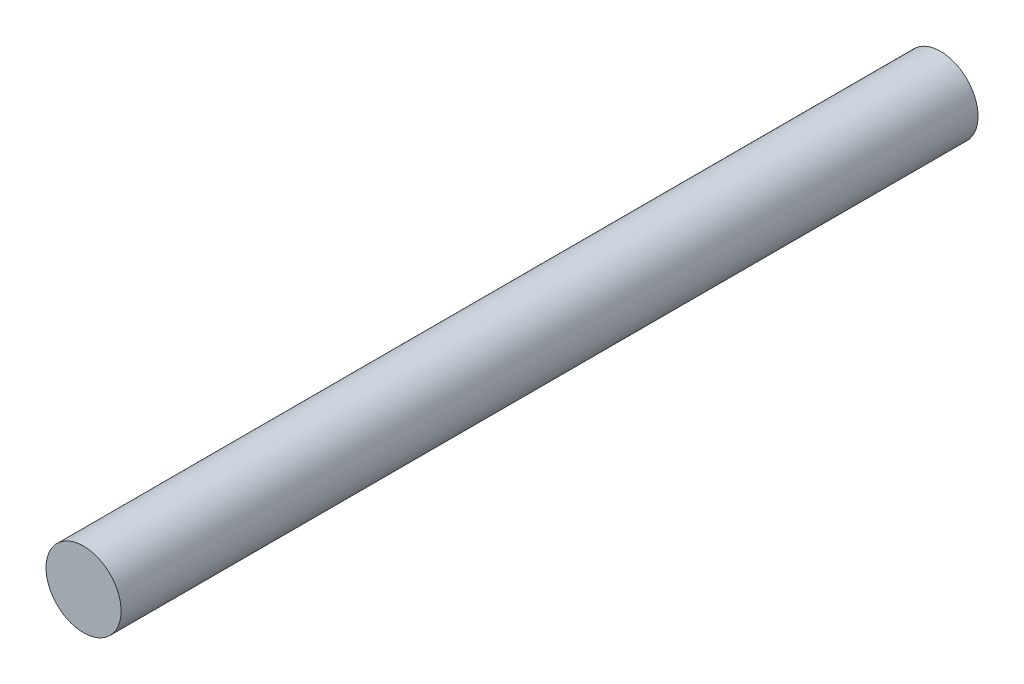
SolidWorks part; units mm, degrees
ref_plane "Front Plane" through (0, 0, 0) normal (0, 0, 1) x (1, 0, 0)
ref_plane "Top Plane" through (0, 0, 0) normal (0, 1, 0) x (1, 0, 0)
ref_plane "Right Plane" through (0, 0, 0) normal (1, 0, 0) x (0, 0, -1)
sketch "Sketch2" plane through (138.3814, 469.4127, -1766.6896) normal (0, 0, -1) x (-0.4312, -0.9023, 0)
  circle A0 centre (61.2968, 103.2892) radius 7.45
  point P2 (61.2968, 103.2892)
  dimension "D1" = 14.9
extrude "Boss-Extrude1" add sketch "Sketch2" along normal blind 170
